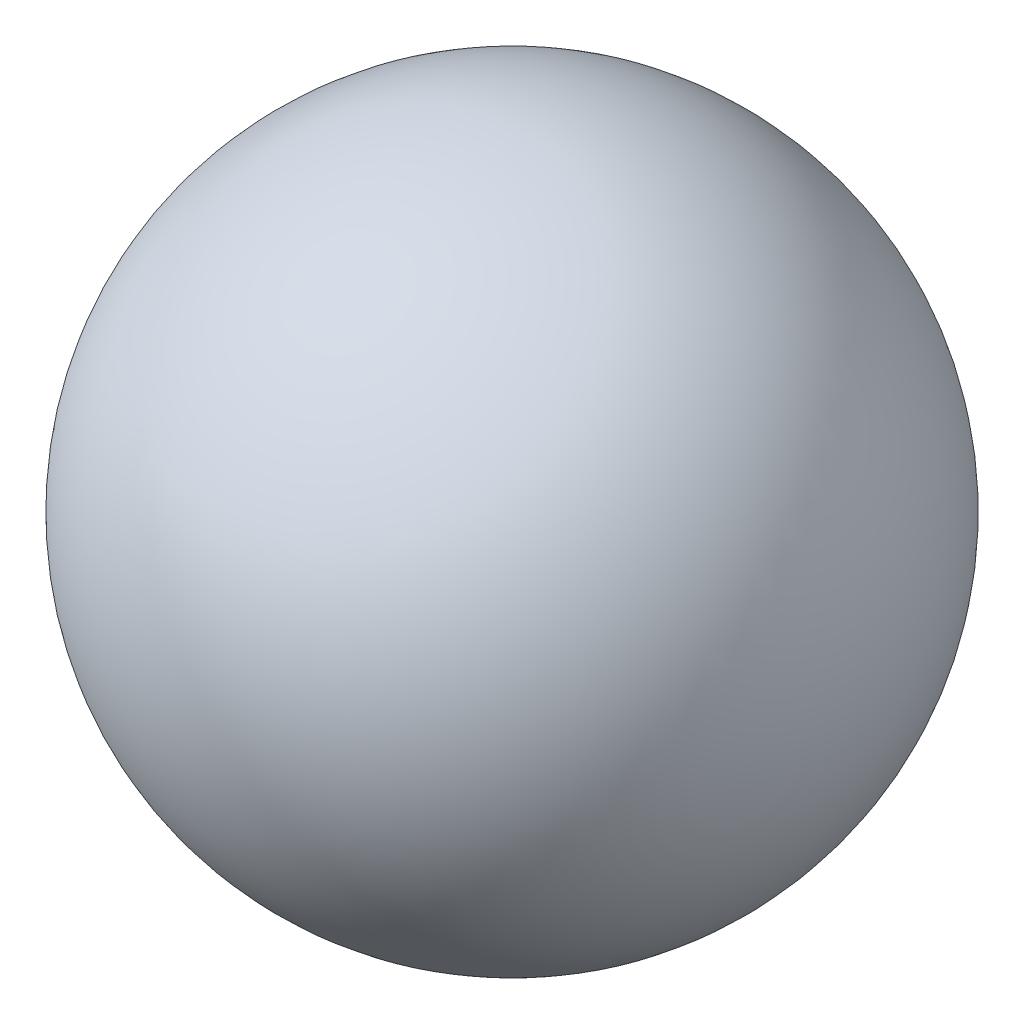
SolidWorks part; units mm, degrees
ref_plane "Front Plane" through (0, 0, 0) normal (0, 0, 1) x (1, 0, 0)
ref_plane "Top Plane" through (0, 0, 0) normal (0, 1, 0) x (1, 0, 0)
ref_plane "Right Plane" through (0, 0, 0) normal (1, 0, 0) x (0, 0, -1)
sketch "Sketch1" plane through (0, 0, 0) normal (0, 0, 1) x (1, 0, 0)
  line L0 (0, 95) -> (0, -95) construction
  line L1 (0, 95) -> (0, -95)
  arc A0 (0, 95) -> (0, -95) centre (0, 0) ccw
  dimension "D2" = 95
  dimension "D1" = 190
revolve "Revolve1" add sketch "Sketch1" angle 360 about L0
